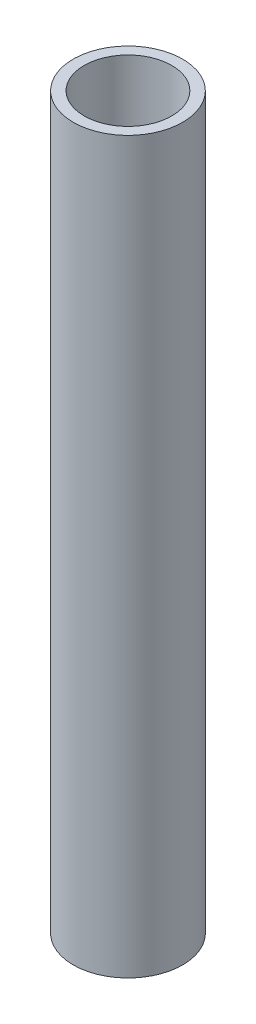
SolidWorks part; units mm, degrees
ref_plane "Front" through (0, 0, 0) normal (0, 0, 1) x (1, 0, 0)
ref_plane "Top" through (0, 0, 0) normal (0, 1, 0) x (1, 0, 0)
ref_plane "Right" through (0, 0, 0) normal (1, 0, 0) x (0, 0, -1)
sketch "Sketch1" plane through (0, 0, 0) normal (0, 1, 0) x (1, 0, 0)
  circle A0 centre (0, 0) radius 15
extrude "Extrude1" add sketch "Sketch1" against normal blind 200
sketch "Sketch2" plane through (0, 0, 0) normal (0, 1, 0) x (1, 0, 0)
  circle A0 centre (0, 0) radius 12
extrude "Cut-Extrude1" cut sketch "Sketch2" against normal blind 190
ref_point "Point1"
ref_plane "Plane1" through (0, -200, 0) normal (0, -1, 0) x (1, 0, 0)
hole_wizard "M6 Tapped Hole2" positions "Sketch7" profile "Sketch6" tap size "M6" standard "ISO"
sketch "Sketch7" plane through (0, -200, 0) normal (0, -1, 0) x (1, 0, 0)
  point P0 (0, 0)
sketch "Sketch6" plane through (0, -200, 0) normal (1, 0, 0) x (0, 0, -1)
  line L0 (0, 0) -> (0, 16.5022)
  line L1 (0, 16.5022) -> (2.5, 15)
  line L2 (2.5, 15) -> (2.5, 12)
  line L3 (2.5, 12) -> (3, 12)
  line L4 (3, 12) -> (3, 0)
  line L5 (3, 0) -> (0, 0)
  line L10 (0, 16.5022) -> (-2.5, 15) construction
  line L11 (0, -6.35) -> (0, 107.95) construction
  dimension "Tap Drill Dia." = 5
  dimension "Tap Drill Depth" = 15
  dimension "Thread Major Dia." = 6
  dimension "Thread Depth" = 12
  dimension "Drill Angle" = 118
